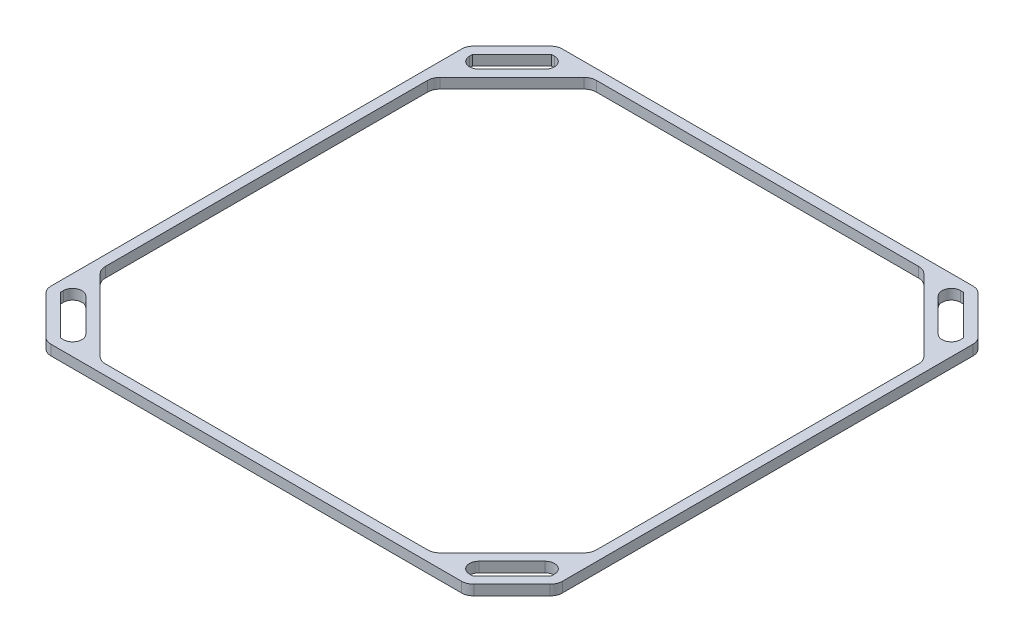
SolidWorks part; units mm, degrees
ref_plane "Front Plane" through (0, 0, 0) normal (0, 0, 1) x (1, 0, 0)
ref_plane "Top Plane" through (0, 0, 0) normal (0, 1, 0) x (1, 0, 0)
ref_plane "Right Plane" through (0, 0, 0) normal (1, 0, 0) x (0, 0, -1)
sketch "Sketch1" plane through (0, 0, 0) normal (0, 1, 0) x (1, 0, 0)
  line L0 (0, 0) -> (0, 45.7586) construction
  line L1 (0, 0) -> (-52.2771, 0) construction
  line L2 (-39.7988, 33.4083) -> (-33.4083, 39.7988)
  line L3 (-33.4083, -39.7988) -> (-29.2929, -39.7988)
  line L4 (-39.7988, -33.4083) -> (-39.7988, -29.2929)
  line L5 (-33.4083, 39.7988) -> (-29.2929, 39.7988)
  line L6 (39.7988, -33.4083) -> (39.7988, -29.2929)
  line L7 (-39.7988, -39.7988) -> (36.6035, 36.6035) construction
  line L8 (-36.6035, 36.6035) -> (39.7988, -39.7988) construction
  line L9 (33.4083, 39.7988) -> (39.7988, 33.4083)
  line L10 (39.7988, -33.4083) -> (33.4083, -39.7988)
  line L11 (-33.4083, -39.7988) -> (-39.7988, -33.4083)
  line L12 (-41.4488, 34.0917) -> (-34.0917, 41.4488)
  line L13 (34.0917, 41.4488) -> (-34.0917, 41.4488)
  line L14 (34.0917, 41.4488) -> (41.4488, 34.0917)
  line L15 (41.4488, -34.0917) -> (41.4488, 34.0917)
  line L16 (41.4488, -34.0917) -> (34.0917, -41.4488)
  line L17 (-34.0917, -41.4488) -> (34.0917, -41.4488)
  line L18 (-34.0917, -41.4488) -> (-41.4488, -34.0917)
  line L19 (-41.4488, 34.0917) -> (-41.4488, -34.0917)
  line L20 (-39.7988, 29.2929) -> (-29.2929, 39.7988)
  line L21 (-39.7988, 26.9594) -> (-26.9594, 39.7988)
  line L22 (29.2929, 39.7988) -> (39.7988, 29.2929)
  line L23 (26.9594, 39.7988) -> (39.7988, 26.9594)
  line L24 (39.7988, -29.2929) -> (29.2929, -39.7988)
  line L25 (39.7988, -26.9594) -> (26.9594, -39.7988)
  line L26 (-29.2929, -39.7988) -> (-39.7988, -29.2929)
  line L27 (-26.9594, -39.7988) -> (-39.7988, -26.9594)
  line L28 (-39.7988, 29.2929) -> (-39.7988, 33.4083)
  line L29 (-26.9594, 39.7988) -> (26.9594, 39.7988)
  line L30 (29.2929, 39.7988) -> (33.4083, 39.7988)
  line L31 (39.7988, 29.2929) -> (39.7988, 33.4083)
  line L32 (39.7988, -26.9594) -> (39.7988, 26.9594)
  line L33 (-39.7988, -26.9594) -> (-39.7988, 26.9594)
  line L34 (-26.9594, -39.7988) -> (26.9594, -39.7988)
  line L35 (29.2929, -39.7988) -> (33.4083, -39.7988)
  point P19 (0, 0)
  point P20 (0, 0)
  point P33 (0, 0)
  point P46 (0, 0)
  dimension "D1" = 1.65
  dimension "D2" = 79.5976
  dimension "D3" = 9.0376
  dimension "D5" = 1.65
  dimension "D6" = 4
  dimension "D7" = 2.91
  dimension "D8" = 1.65
  dimension "D4" = 4
  dimension "D9" = 4
extrude "Boss-Extrude1" add sketch "Sketch1" along normal blind 1.65
fillet "Fillet1" radius 2 4 edges at (-41.4488, 0.825, -34.0917) (-34.0917, 0.825, -41.4488) (-39.7988, 0.825, -26.9594) (-26.9594, 0.825, -39.7988)
fillet "Fillet2" radius 2 12 edges at (-26.9594, 0.825, 39.7988) (-39.7988, 0.825, 26.9594) (-41.4488, 0.825, 34.0917) (-34.0917, 0.825, 41.4488) (34.0917, 0.825, 41.4488) (41.4488, 0.825, 34.0917) (26.9594, 0.825, 39.7988) (39.7988, 0.825, 26.9594) (39.7988, 0.825, -26.9594) (26.9594, 0.825, -39.7988) (41.4488, 0.825, -34.0917) (34.0917, 0.825, -41.4488)
fillet "Fillet3" radius 1.5 8 edges at (29.2929, 0.825, 39.7988) (39.7988, 0.825, 29.2929) (-29.2929, 0.825, 39.7988) (-39.7988, 0.825, 29.2929) (-39.7988, 0.825, -29.2929) (-29.2929, 0.825, -39.7988) (39.7988, 0.825, -29.2929) (29.2929, 0.825, -39.7988)
